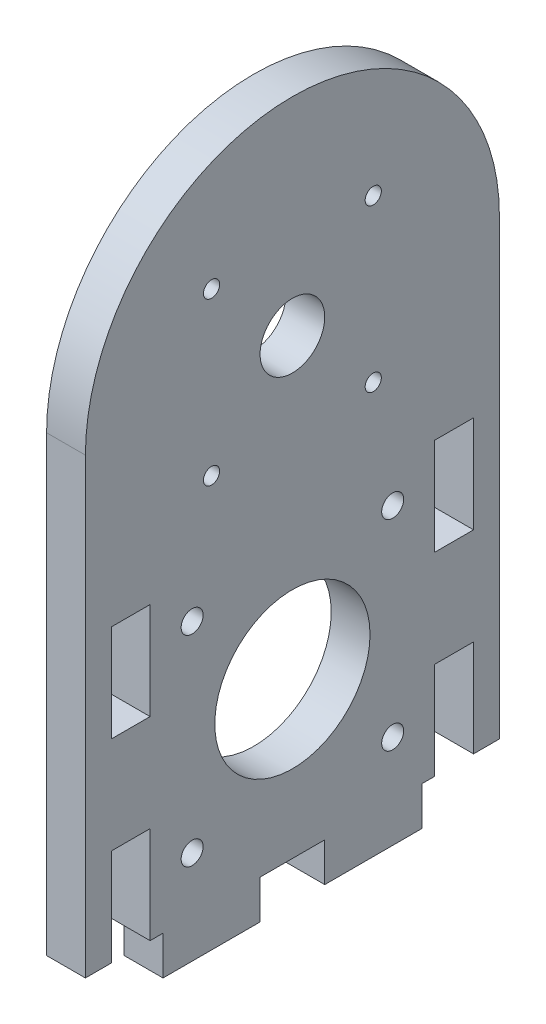
SolidWorks part; units mm, degrees
material "6061-T6 (SS)"
ref_plane "Alzado" through (0, 0, 0) normal (0, 0, 1) x (1, 0, 0)
ref_plane "Planta" through (0, 0, 0) normal (0, 1, 0) x (1, 0, 0)
ref_plane "Vista lateral" through (0, 0, 0) normal (1, 0, 0) x (0, 0, -1)
sketch "Croquis1" plane through (0, 0, 0) normal (1, 0, 0) x (0, 0, -1)
  line L0 (-32, -35) -> (-32, 35)
  line L1 (32, 35) -> (32, -35)
  line L2 (32, -35) -> (-32, -35)
  line L3 (0, -35) -> (0, 35) construction
  arc A0 (-32, 35) -> (32, 35) centre (0, 35) cw
  circle A1 centre (0, 35) radius 5
  circle A2 centre (0, -11) radius 12
  point P6 (0, 0)
  dimension "D3" = 10
  dimension "D5" = 24
  dimension "D1" = 70
  dimension "D2" = 64
  dimension "D4" = 24
extrude "Saliente-Extruir1" add sketch "Croquis1" along normal mid plane 6
hole_wizard "Taladro de margen para M32" positions "Croquis4" profile "Croquis5" hole size "M3" standard "Ansi Metric" end condition up to next
sketch "Croquis4" plane through (3, 0, 0) normal (1, 0, 0) x (0, 0, -1)
  point P0 (-15.5, 4.5)
  point P2 (-15.5, -26.5)
  point P4 (15.5, -26.5)
  point P6 (15.5, 4.5)
sketch "Croquis5" plane through (3, 4.5, 15.5) normal (0, 1, 0) x (0, 0, -1)
  line L0 (0, 0) -> (0, 6)
  line L1 (0, 6) -> (1.7, 6)
  line L2 (1.7, 6) -> (1.7, 0)
  line L5 (1.7, 0) -> (0, 0)
  line L11 (0, -6.35) -> (0, 107.95) construction
  dimension "Diámetro de taladro hasta el siguiente" = 3.4
  dimension "Profundidad de taladro hasta el siguiente" = 6
hole_wizard "Taladro roscado M3x0.51" positions "Croquis6" profile "Croquis7" tap size "M3x0.5" standard "Ansi Metric" end condition up to next
sketch "Croquis6" plane through (-3, 0, 0) normal (-1, 0, 0) x (0, 0, 1)
  point P0 (-12.5, 22.5)
  point P3 (-12.5, 47.5)
  point P6 (12.5, 47.5)
  point P9 (12.5, 22.5)
sketch "Croquis7" plane through (-3, 22.5, -12.5) normal (0, 1, 0) x (0, 0, 1)
  line L0 (0, 0) -> (0, 6)
  line L1 (0, 6) -> (1.25, 6)
  line L2 (1.25, 6) -> (1.25, 0)
  line L5 (1.25, 0) -> (0, 0)
  line L11 (0, -6.35) -> (0, 107.95) construction
  dimension "Diámetro de perforador para roscar hasta el siguiente" = 2.5
  dimension "Profundidad de perforador para roscar hasta el siguiente" = 6
cosmetic thread "Rosca de taladro1" parameters "D2"=3
cosmetic thread "Rosca de taladro2" parameters "D2"=3
cosmetic thread "Rosca de taladro3" parameters "D2"=3
cosmetic thread "Rosca de taladro4" parameters "D2"=3
sketch "Croquis8" plane through (3, 0, 0) normal (1, 0, 0) x (0, 0, -1)
  line L0 (0, 0) -> (0, -35) construction
  line L1 (-28, 10) -> (-22, 10)
  line L2 (-28, 10) -> (-28, -5)
  line L3 (-28, -5) -> (-22, -5)
  line L4 (-22, 10) -> (-22, -5)
  line L5 (-28, -20) -> (-22, -20)
  line L6 (-28, -20) -> (-28, -35)
  line L7 (-28, -35) -> (-22, -35)
  line L8 (-22, -20) -> (-22, -35)
  line L9 (-32, -35) -> (32, -35) construction
  line L10 (28, -35) -> (22, -35)
  line L11 (22, -20) -> (22, -35)
  line L12 (28, -20) -> (22, -20)
  line L13 (28, -20) -> (28, -35)
  line L14 (28, -5) -> (22, -5)
  line L15 (22, 10) -> (22, -5)
  line L16 (28, 10) -> (22, 10)
  line L17 (28, 10) -> (28, -5)
  dimension "D1" = 15
  dimension "D2" = 15
  dimension "D3" = 6
  dimension "D4" = 22
extrude "Cortar-Extruir1" cut sketch "Croquis8" against normal through all
sketch "Croquis9" plane through (3, 0, 0) normal (1, 0, 0) x (0, 0, -1)
  line L0 (-22, -35) -> (22, -35) construction
  line L1 (-20, -35) -> (-5, -35)
  line L2 (-20, -35) -> (-20, -41)
  line L3 (-20, -41) -> (-5, -41)
  line L4 (-5, -35) -> (-5, -41)
  line L5 (-5, -38) -> (5, -38) construction
  line L6 (5, -35) -> (20, -35)
  line L7 (5, -35) -> (5, -41)
  line L8 (5, -41) -> (20, -41)
  line L9 (20, -35) -> (20, -41)
  point P12 (0, -38)
  dimension "D1" = 15
  dimension "D2" = 10
  dimension "D3" = 6
extrude "Saliente-Extruir3" add sketch "Croquis9" against normal through all
